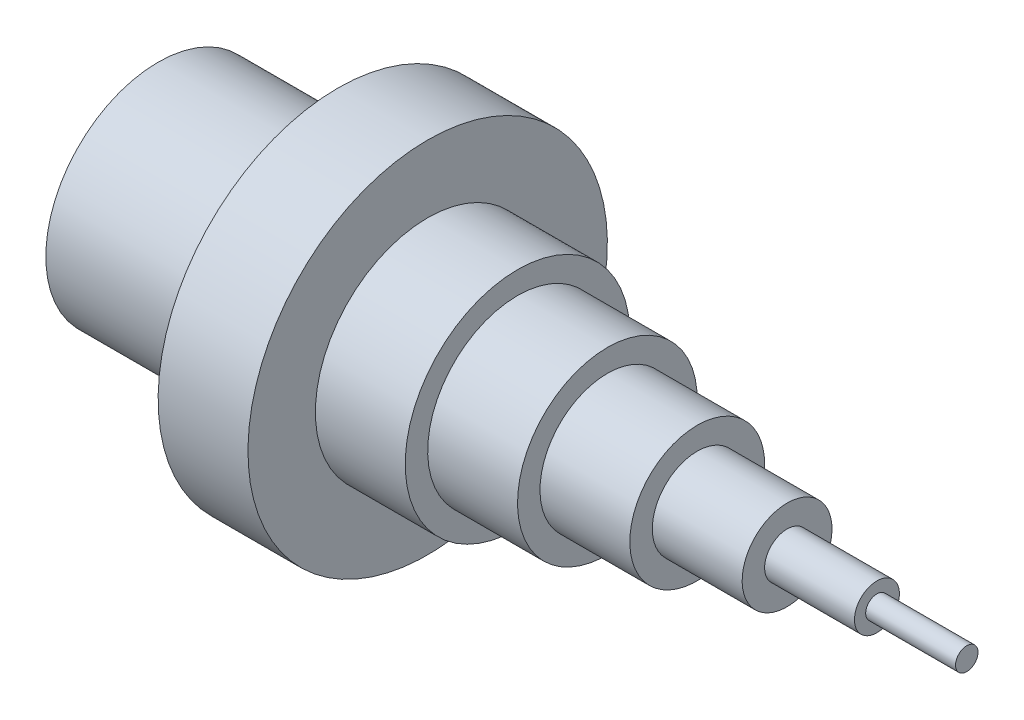
SolidWorks part; units mm, degrees
ref_plane "Front Plane" through (0, 0, 0) normal (0, 0, 1) x (1, 0, 0)
ref_plane "Top Plane" through (0, 0, 0) normal (0, 1, 0) x (1, 0, 0)
ref_plane "Right Plane" through (0, 0, 0) normal (1, 0, 0) x (0, 0, -1)
sketch "Sketch1" plane through (0, 0, 0) normal (0, 0, 1) x (1, 0, 0)
  line L0 (0, 40) -> (20, 40)
  line L1 (20, 40) -> (20, 25)
  line L2 (20, 25) -> (40, 25)
  line L3 (40, 25) -> (40, 20)
  line L4 (40, 20) -> (60, 20)
  line L5 (60, 20) -> (60, 15)
  line L6 (60, 15) -> (80, 15)
  line L7 (80, 15) -> (80, 10)
  line L8 (80, 10) -> (100, 10)
  line L9 (100, 10) -> (100, 5)
  line L10 (100, 5) -> (120, 5)
  line L11 (120, 5) -> (120, 2.5)
  line L12 (120, 2.5) -> (140, 2.5)
  line L13 (140, 2.5) -> (140, 0)
  line L14 (140, 0) -> (0, 0)
  line L15 (0, 40) -> (0, 25)
  line L16 (0, 25) -> (-40, 25)
  line L17 (-40, 25) -> (-40, 20)
  line L18 (-40, 20) -> (0, 20)
  line L19 (0, 20) -> (0, 0)
  point P2 (40, 22.5)
  dimension "D1" = 20
  dimension "D2" = 20
  dimension "D3" = 2.5
  dimension "D4" = 2.5
  dimension "D5" = 5
  dimension "D6" = 40
  dimension "D7" = 15
revolve "Revolve1" add sketch "Sketch1" angle 360 about L14
